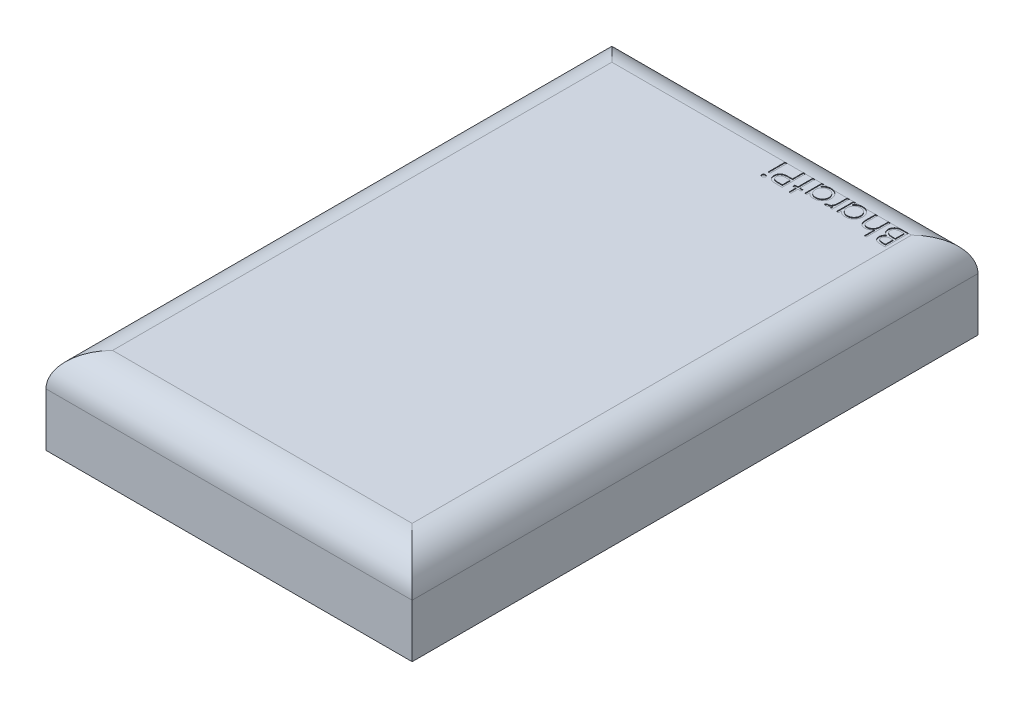
SolidWorks part; units mm, degrees
ref_plane "Front Plane" through (0, 0, 0) normal (0, 0, 1) x (1, 0, 0)
ref_plane "Top Plane" through (0, 0, 0) normal (0, 1, 0) x (1, 0, 0)
ref_plane "Right Plane" through (0, 0, 0) normal (1, 0, 0) x (0, 0, -1)
sketch "Sketch1" plane through (0, 0, 0) normal (0, 1, 0) x (1, 0, 0)
  line L1 (-27.5, -42.5) -> (27.5, -42.5)
  line L2 (-27.5, -42.5) -> (-27.5, 42.5)
  line L3 (-27.5, 42.5) -> (27.5, 42.5)
  line L4 (27.5, -42.5) -> (27.5, 42.5)
  line L5 (-27.5, -42.5) -> (27.5, 42.5) construction
  line L6 (-27.5, 42.5) -> (27.5, -42.5) construction
  point P0 (0, 0)
  dimension "D1" = 55
  dimension "D2" = 85
extrude "Boss-Extrude1" add sketch "Sketch1" along normal blind 13
fillet "Fillet1" radius 5 4 edges at (0, 13, 42.5) (-27.5, 13, 0) (0, 13, -42.5) (27.5, 13, 0)
sketch "Sketch2" plane through (0, 13, 0) normal (0, 1, 0) x (1, 0, 0)
  text T0 "BharatPi\r\n"
  point P1 (0, 0)
  point P2 (-8.1404, 25.5543)
  point P3 (0, -0.7235)
  point P4 (0, 0)
extrude "Cut-Extrude1" cut sketch "Sketch2" against normal blind 0.1
